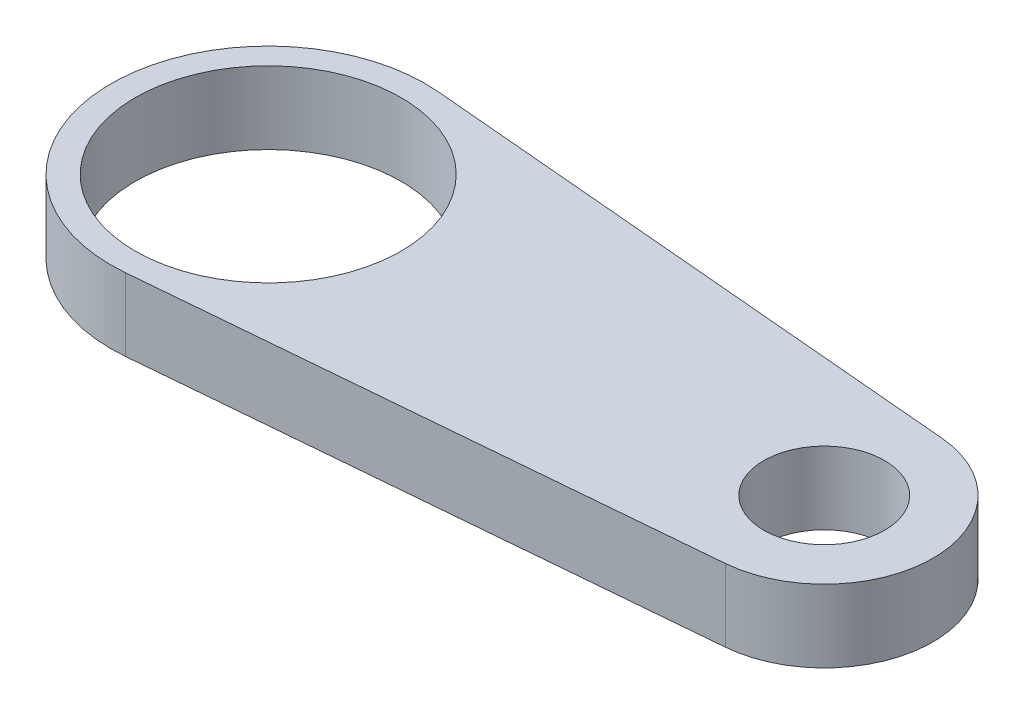
SolidWorks part; units mm, degrees
ref_plane "Front Plane" through (0, 0, 0) normal (0, 0, 1) x (1, 0, 0)
ref_plane "Top Plane" through (0, 0, 0) normal (0, 1, 0) x (1, 0, 0)
ref_plane "Right Plane" through (0, 0, 0) normal (1, 0, 0) x (0, 0, -1)
sketch "Sketch1" plane through (0, 0, 0) normal (0, 1, 0) x (1, 0, 0)
  line L1 (2.2609, 25.9015) -> (93.5652, 17.9318)
  line L2 (2.2609, -25.9015) -> (93.5652, -17.9318)
  circle A0 centre (0, 0) radius 22
  arc A1 (2.2609, 25.9015) -> (2.2609, -25.9015) centre (0, 0) ccw
  circle A2 centre (92, 0) radius 10
  arc A3 (93.5652, -17.9318) -> (93.5652, 17.9318) centre (92, 0) ccw
  dimension "D1" = 26
  dimension "D2" = 18
  dimension "D3" = 20
  dimension "D4" = 44
  dimension "D5" = 92
extrude "Boss-Extrude1" add sketch "Sketch1" along normal blind 12
sketch "Sketch2" plane through (0, 12, 0) normal (0, 1, 0) x (1, 0, 0)
  line L0 (0, 0) -> (92, 0) construction
